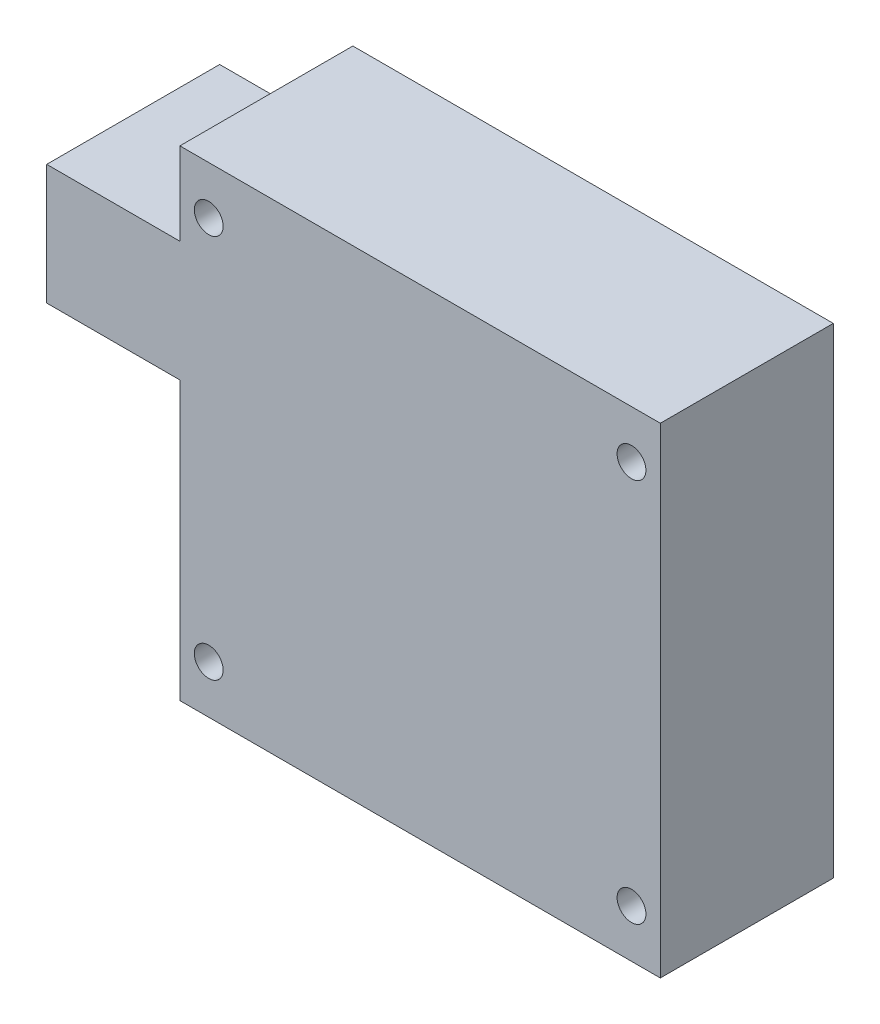
SolidWorks part; units mm, degrees
ref_plane "前视基准面" through (0, 0, 0) normal (0, 0, 1) x (1, 0, 0)
ref_plane "上视基准面" through (0, 0, 0) normal (0, 1, 0) x (1, 0, 0)
ref_plane "右视基准面" through (0, 0, 0) normal (1, 0, 0) x (0, 0, -1)
sketch "草图1" plane through (0, 0, 0) normal (0, 0, 1) x (1, 0, 0)
  line L1 (25, -25) -> (-25, -25)
  line L2 (25, -25) -> (25, 25)
  line L3 (25, 25) -> (-25, 25)
  line L4 (-25, -25) -> (-25, 25)
  line L5 (25, -25) -> (-25, 25) construction
  line L6 (25, 25) -> (-25, -25) construction
  line L7 (22, -20) -> (-22, -20) construction
  line L8 (22, -20) -> (22, 20) construction
  line L9 (22, 20) -> (-22, 20) construction
  line L10 (-22, -20) -> (-22, 20) construction
  line L11 (22, -20) -> (-22, 20) construction
  line L12 (22, 20) -> (-22, -20) construction
  circle A0 centre (-22, 20) radius 1.5
  circle A1 centre (-22, -20) radius 1.5
  circle A2 centre (22, 20) radius 1.5
  circle A3 centre (22, -20) radius 1.5
  point P0 (0, 0)
  point P6 (0, 0)
  dimension "D3" = 3
  dimension "D1" = 50
  dimension "D2" = 50
  dimension "D4" = 40
  dimension "D5" = 44
extrude "凸台-拉伸1" add sketch "草图1" along normal blind 18
sketch "草图2" plane through (0, 0, 18) normal (0, 0, 1) x (1, 0, 0)
  line L0 (-25, 25) -> (-25, -25) construction
  line L1 (-25, 16.4046) -> (-38.8601, 16.4046)
  line L2 (-25, 16.4046) -> (-25, 3.8995)
  line L3 (-25, 3.8995) -> (-38.8601, 3.8995)
  line L4 (-38.8601, 16.4046) -> (-38.8601, 3.8995)
extrude "凸台-拉伸2" add sketch "草图2" against normal up to surface (18 mm away) up to face at (0, 0, 0)
